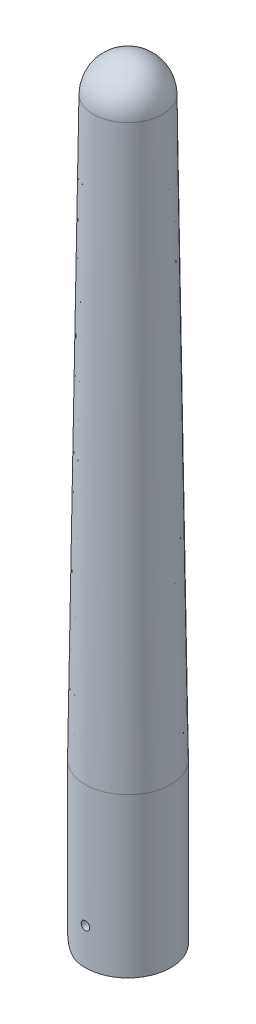
SolidWorks part; units mm, degrees
ref_plane "Front Plane" through (0, 0, 0) normal (0, 0, 1) x (1, 0, 0)
ref_plane "Top Plane" through (0, 0, 0) normal (0, 1, 0) x (1, 0, 0)
ref_plane "Right Plane" through (0, 0, 0) normal (1, 0, 0) x (0, 0, -1)
sketch "Sketch2" plane through (0, 0, 0) normal (0, 0, 1) x (1, 0, 0)
  line L0 (0, 0) -> (0, 105.1939) construction
  line L1 (0, 0) -> (5, 0)
  line L2 (5, 0) -> (5, 19.05)
  line L3 (5, 19.05) -> (4.0564, 86.424)
  line L4 (0, 90.424) -> (0, 0)
  arc A0 (4.0564, 86.424) -> (0, 90.424) centre (0, 86.3672) ccw
  dimension "D1" = 19.05
  dimension "D2" = 10
  dimension "D3" = 90.424
  dimension "D4" = 4
revolve "Revolve1" add sketch "Sketch2" angle 360 about L0
sketch "Sketch6" plane through (0, 0, 0) normal (0, 0, 1) x (1, 0, 0)
  line L1 (-4, 3.5) -> (-4, 7)
  line L3 (-5, 19.05) -> (-5, 0) construction
  line L4 (-5, 0) -> (-5, 8)
  line L5 (-4, 7) -> (-5, 8)
  line L6 (-5, 0) -> (5, 0) construction
  line L7 (-1, 0.5) -> (5, 0.5)
  line L8 (5, 0) -> (5, 19.05) construction
  line L9 (5, 0.5) -> (5, 0)
  line L10 (5, 0) -> (-5, 0)
  arc A0 (-1, 0.5) -> (-4, 3.5) centre (-1, 3.5) cw
  dimension "D1" = 45
  dimension "D2" = 1
  dimension "D3" = 4
  dimension "D4" = 8
  dimension "D5" = 0.5
extrude "Cut-Extrude1" cut sketch "Sketch6" against normal through all both and the other way through all
sketch "Sketch7" plane through (0, 0, 0) normal (0, 0, 1) x (1, 0, 0)
  circle A0 centre (0, 4.7625) radius 0.5
  dimension "D1" = 1
  dimension "D2" = 4.7625
extrude "Cut-Extrude2" cut sketch "Sketch7" against normal through all both and the other way through all
sketch "Sketch8" plane through (0, 0.5, 0) normal (0, -1, 0) x (1, 0, 0)
  line L0 (0, 3) -> (-5, 3)
  line L1 (-5, 3) -> (-5, -3)
  line L2 (-5, -3) -> (0, -3)
  arc A0 (0, -3) -> (0, 3) centre (0, 0) ccw
  arc A1 (-4, 3) -> (-4, -3) centre (0, 0) ccw construction
extrude "Cut-Extrude3" cut sketch "Sketch8" against normal up to vertex (6.5 mm away)
